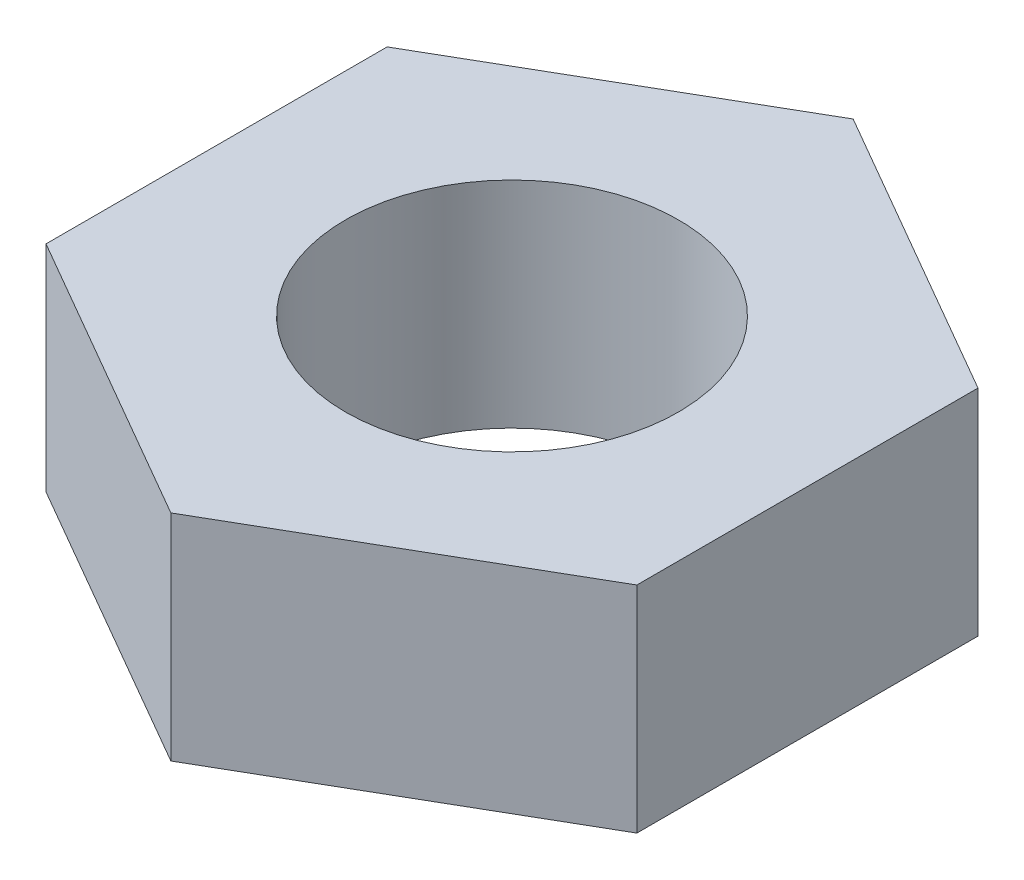
SolidWorks part; units mm, degrees
ref_plane "Front Plane" through (0, 0, 0) normal (0, 0, 1) x (1, 0, 0)
ref_plane "Top Plane" through (0, 0, 0) normal (0, 1, 0) x (1, 0, 0)
ref_plane "Right Plane" through (0, 0, 0) normal (1, 0, 0) x (0, 0, -1)
sketch "Sketch1" plane through (0, 0, 0) normal (0, 1, 0) x (1, 0, 0)
  line L1 (0, 3.1754) -> (-2.75, 1.5877)
  line L2 (-2.75, 1.5877) -> (-2.75, -1.5877)
  line L3 (-2.75, -1.5877) -> (0, -3.1754)
  line L4 (0, -3.1754) -> (2.75, -1.5877)
  line L5 (2.75, -1.5877) -> (2.75, 1.5877)
  line L6 (2.75, 1.5877) -> (0, 3.1754)
  circle A0 centre (0, 0) radius 2.75 construction
  circle A1 centre (0, 0) radius 1.55
extrude "Boss-Extrude1" add sketch "Sketch1" along normal blind 2
